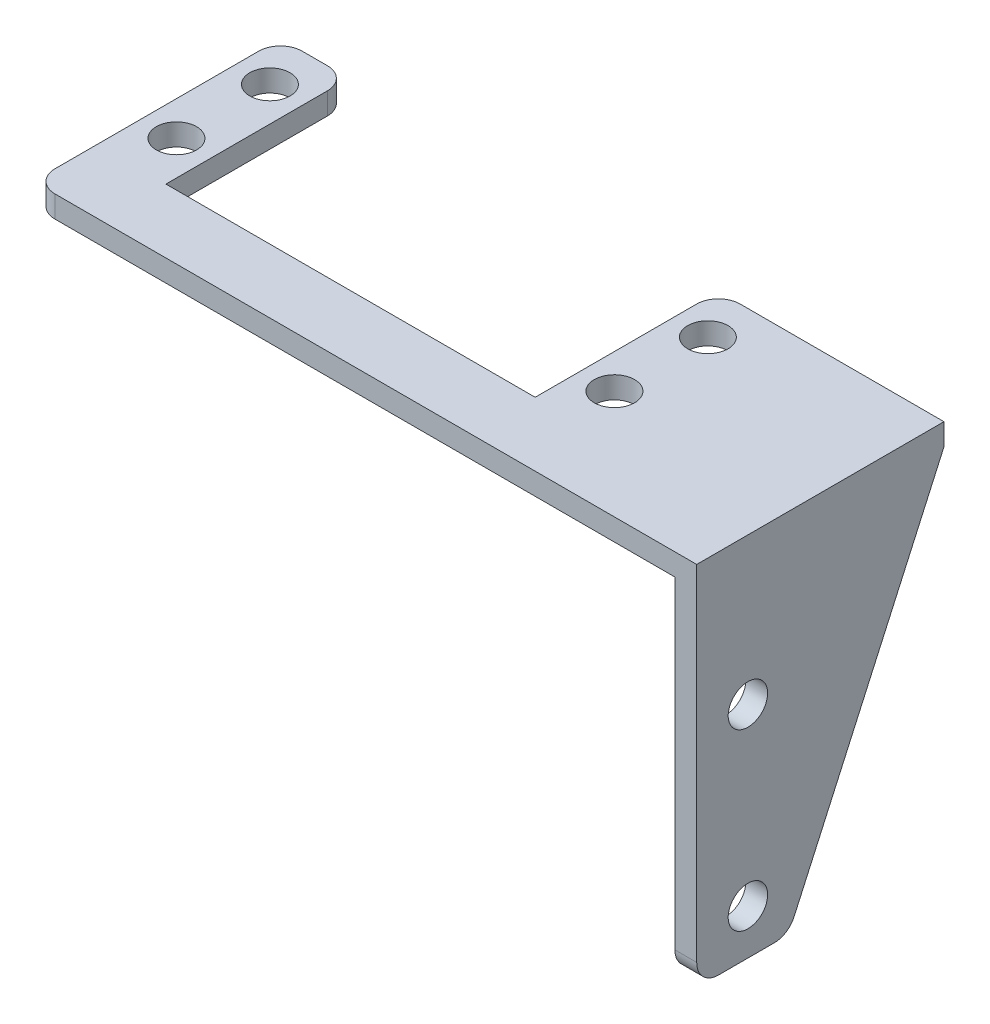
SolidWorks part; units mm, degrees
ref_plane "Front Plane" through (0, 0, 0) normal (0, 0, 1) x (1, 0, 0)
ref_plane "Top Plane" through (0, 0, 0) normal (0, 1, 0) x (1, 0, 0)
ref_plane "Right Plane" through (0, 0, 0) normal (1, 0, 0) x (0, 0, -1)
sketch "Sketch1" plane through (0, 0, 0) normal (0, 1, 0) x (1, 0, 0)
  line L0 (20.15, 0) -> (-20.15, 0)
  line L1 (-20.15, 0) -> (-20.15, 20)
  line L2 (-20.15, 20) -> (-27.65, 20)
  line L3 (-27.65, 20) -> (-27.65, -6.985)
  line L4 (-27.65, -6.985) -> (27.65, -6.985)
  line L5 (0, 0) -> (0, -6.985)
  line L6 (20.15, 20) -> (42.3837, 20)
  line L7 (42.3837, 20) -> (42.3837, -6.985)
  line L8 (20.15, 0) -> (20.15, 20)
  line L9 (27.65, -6.985) -> (42.3837, -6.985)
  circle A0 centre (-23.9, 15.1) radius 2.2
  circle A1 centre (-23.9, 4.9) radius 2.2
  circle A2 centre (23.9, 4.9) radius 2.2
  circle A3 centre (23.9, 15.1) radius 2.2
  point P0 (0, 0)
  dimension "D3" = 4.4
  dimension "D6" = 4.4
  dimension "D1" = 3.75
  dimension "D2" = 3.75
  dimension "D4" = 4.9
  dimension "D5" = 10.2
  dimension "D7" = 4.9
  dimension "D8" = 6.985
  dimension "D9" = 23.9
  dimension "D10" = 0
  dimension "D11" = 22.2338
extrude "Boss-Extrude1" add sketch "Sketch1" along normal blind 2.3813
sketch "Sketch3" plane through (42.3837, 0, 0) normal (1, 0, 0) x (0, 0, -1)
  line L0 (20, 0) -> (3.015, -37.6187)
  line L1 (20, 2.3813) -> (-6.985, 2.3813)
  line L2 (20, 2.3813) -> (20, 0)
  line L3 (3.015, -37.6187) -> (-6.985, -37.6187)
  line L4 (-6.985, 2.3813) -> (-6.985, -37.6187)
  line L5 (-6.985, 2.3813) -> (-6.985, 0) construction
  point P10 (-6.985, 1.1906)
  dimension "D1" = 10
  dimension "D2" = 0
  dimension "D3" = 40
extrude "Boss-Extrude3" add sketch "Sketch3" along normal blind 2.3813
sketch "Sketch4" plane through (44.765, 0, 0) normal (1, 0, 0) x (0, 0, -1)
  line L0 (20, 2.3813) -> (-6.985, 2.3813) construction
  line L1 (-6.985, 2.3813) -> (-6.985, -37.6187) construction
  circle A0 centre (-1.397, -13.646) radius 2.1526
  circle A1 centre (-1.397, -32.696) radius 2.1526
  dimension "D4" = 4.3053
  dimension "D5" = 4.3053
  dimension "D1" = 16.0272
  dimension "D2" = 5.588
  dimension "D3" = 19.05
  dimension "D6" = 5.588
extrude "Cut-Extrude1" cut sketch "Sketch4" against normal up to surface (2.3813 mm away) up to face at (42.3837, -18.8094, -2.2613)
fillet "Fillet2" radius 2.3813 6 edges at (20.15, 1.1906, -20) (-20.15, 1.1906, -20) (-27.65, 1.1906, 6.985) (-27.65, 1.1906, -20) (43.5744, -37.6187, 6.985) (43.5744, -37.6187, -3.015)
